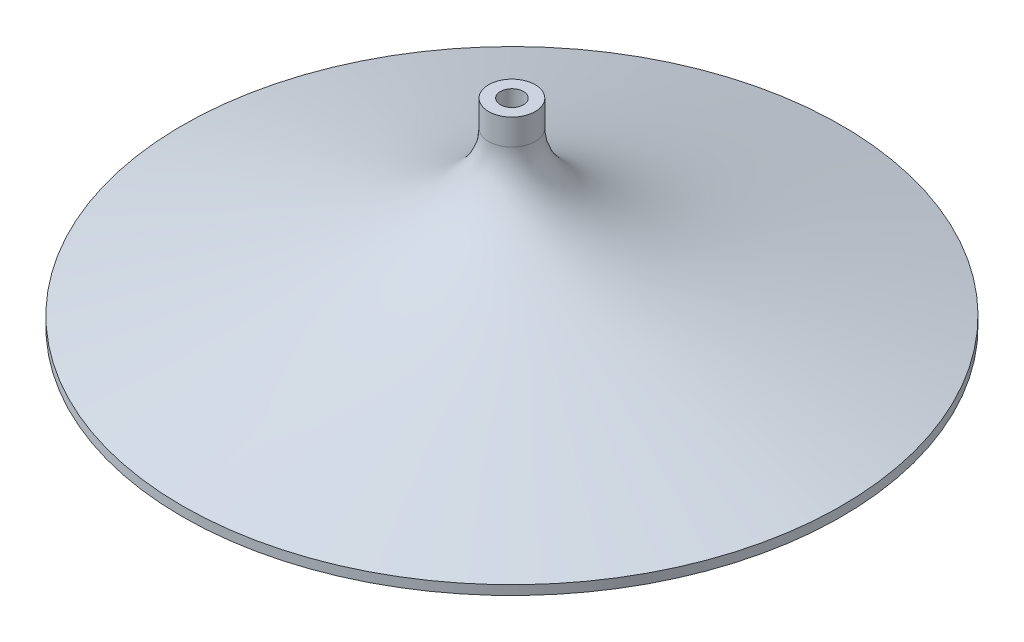
SolidWorks part; units mm, degrees
ref_plane "Front Plane" through (0, 0, 0) normal (0, 0, 1) x (1, 0, 0)
ref_plane "Top Plane" through (0, 0, 0) normal (0, 1, 0) x (1, 0, 0)
ref_plane "Right Plane" through (0, 0, 0) normal (1, 0, 0) x (0, 0, -1)
sketch "Sketch1" plane through (0, 0, 0) normal (0, 0, 1) x (1, 0, 0)
  line L0 (100, 28.0207) -> (100, -22.3317) construction
  line L1 (0, -55) -> (0, 55) construction
  line L2 (-28.6183, 60) -> (29.7327, 60) construction
  line L3 (55, 0) -> (-55, 0) construction
  line L4 (3.5, 73.8648) -> (3.5, -32.4182) construction
  line L5 (7.0573, 68.5095) -> (7.0573, 37.8399) construction
  line L6 (100, 2.8445) -> (100, 0)
  line L7 (3.5, 39.9595) -> (3.5, 20.6921) construction
  line L8 (95.2447, 0) -> (104.7553, 0) construction
  line L9 (7.0573, 52.125) -> (7.0573, 60)
  line L10 (7.0573, 60) -> (3.5, 60)
  line L11 (3.5, 60) -> (3.5, 41.1639)
  line L12 (0, 82.92) -> (0, -20.3033) construction
  spline S0 degree 3 poles (100, 2.8445) (58.2634, 15.906) (27.9536, 25.1951) (7.0573, 41.2144) (7.0573, 52.125) knots 0 0 0 0 0.52587 1 1 1 1
  spline S1 degree 3 poles (100, 0) (90.3128, 0) (43.1197, 15.0736) (9.4386, 32.1161) (3.5, 40.9288) (3.5, 41.1639) knots 0 0 0 0 0.641469 0.741469 1 1 1 1
  dimension "D1" = 100
  dimension "D2" = 60
  dimension "D3" = 3.5
revolve "Revolve1" add sketch "Sketch1" angle 360 about L12
sketch "Sketch2" plane through (0, 0, 0) normal (0, 1, 0) x (1, 0, 0)
  line L0 (-63.436, 0) -> (63.436, 0) construction
  line L1 (0, -63.436) -> (0, 63.436) construction
  circle A0 centre (-50, -50) radius 3
  circle A3 centre (50, -50) radius 3
  circle A4 centre (50, 50) radius 3
  circle A5 centre (-50, 50) radius 3
  dimension "D2" = 50
  dimension "D3" = 6
  dimension "D1" = 50
  dimension "D4" = 2
  dimension "D5" = 2
extrude "Cut-Extrude2" cut sketch "Sketch2" along normal blind 10
